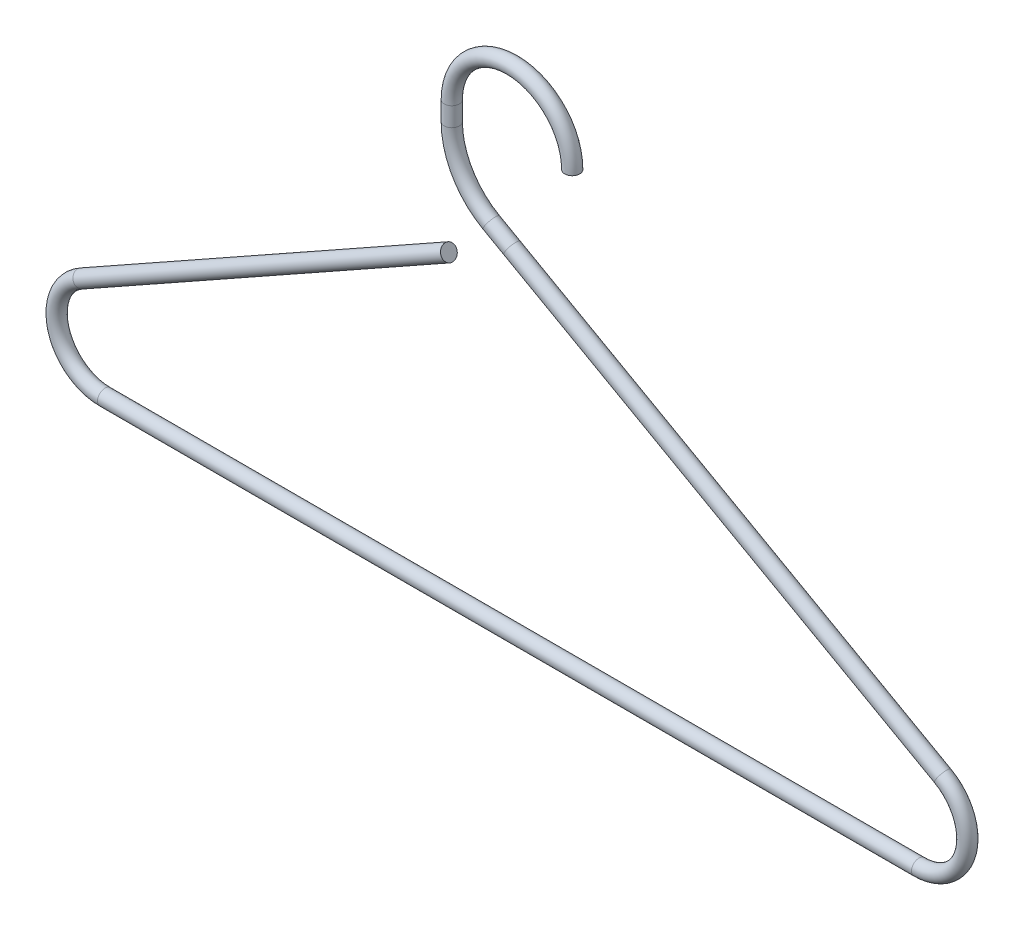
SolidWorks part; units mm, degrees
ref_plane "Front Plane" through (0, 0, 0) normal (0, 0, 1) x (1, 0, 0)
ref_plane "Top Plane" through (0, 0, 0) normal (0, 1, 0) x (1, 0, 0)
ref_plane "Right Plane" through (0, 0, 0) normal (1, 0, 0) x (0, 0, -1)
sketch "Sketch1" plane through (0, 0, 0) normal (0, 0, 1) x (1, 0, 0)
  line L1 (-196.6414, -47.9509) -> (196.6414, -47.9509) construction
  line L2 (196.6414, -47.9509) -> (0, 62.4942) construction
  line L3 (0, -47.9509) -> (0, 131.8779) construction
  line L4 (-20, 95.1284) -> (-20, 88.807)
  line L5 (0, 62.4942) -> (-6.8522, 66.3428)
  line L6 (-20.9631, 50.7201) -> (-196.6414, -47.9509) construction
  line L7 (-20, 95.1284) -> (19.9996, 95.0076) construction
  line L8 (-20.9631, 50.7201) -> (-143.0736, -17.8642)
  line L9 (-135.2026, -47.9509) -> (135.2026, -47.9509)
  line L10 (143.0736, -17.8642) -> (0, 62.4942)
  arc A0 (-143.0736, -17.8642) -> (-135.2026, -47.9509) centre (-135.2026, -31.878) ccw
  arc A1 (143.0736, -17.8642) -> (135.2026, -47.9509) centre (135.2026, -31.878) cw
  arc A2 (19.9996, 95.0076) -> (-20, 95.1284) centre (0, 95.1284) ccw
  arc A3 (-20, 88.807) -> (-6.8522, 66.3428) centre (5.7651, 88.807) ccw
  point P12 (-20.9631, 50.7201)
  dimension "D1" = 20
sketch "Sketch2" plane through (0, 0, 0) normal (1, 0, 0) x (0, 0, -1)
  line L0 (0, 50.7201) -> (0, -47.9509) construction
  line L1 (0, -17.8642) -> (0, -47.9509) construction
  circle A0 centre (0, -47.9509) radius 2.5
  dimension "D1" = 5
sweep "Sweep1" add profiles "Sketch2" path "Sketch1"
